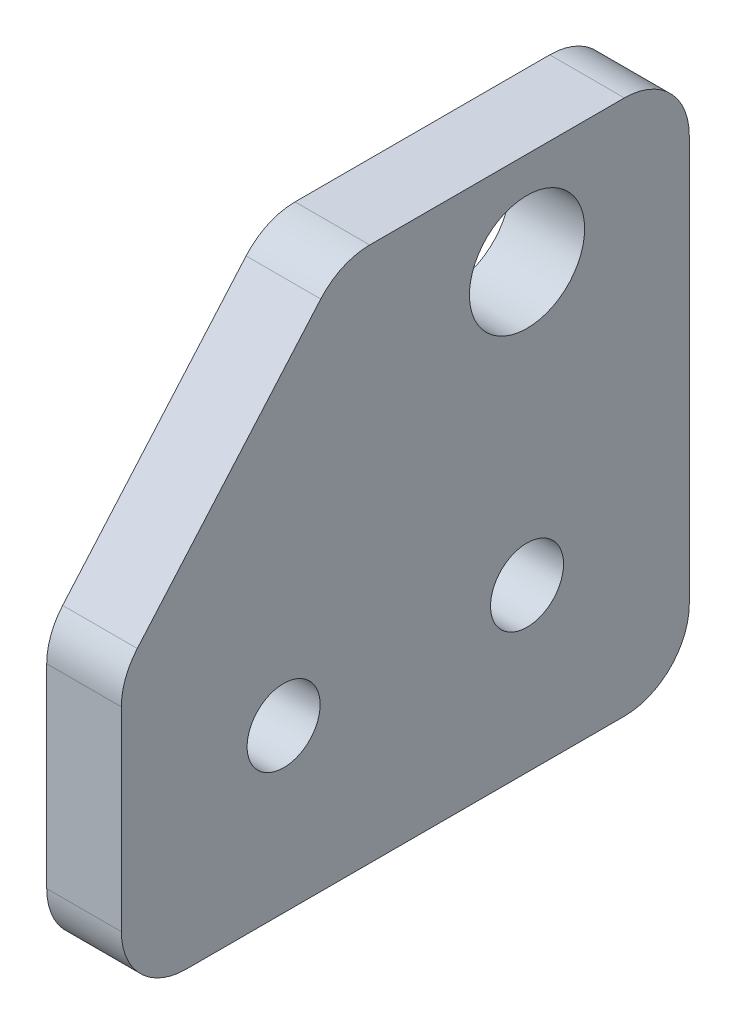
SolidWorks part; units mm, degrees
ref_plane "Front Plane" through (0, 0, 0) normal (0, 0, 1) x (1, 0, 0)
ref_plane "Top Plane" through (0, 0, 0) normal (0, 1, 0) x (1, 0, 0)
ref_plane "Right Plane" through (0, 0, 0) normal (1, 0, 0) x (0, 0, -1)
sketch "Sketch1" plane through (0, 0, 0) normal (1, 0, 0) x (0, 0, -1)
  line L0 (0, -10) -> (0, 23) construction
  line L1 (10, 0) -> (-25, 0) construction
  line L2 (-21, -10) -> (6, -10)
  line L3 (10, -6) -> (10, 19)
  line L4 (6, 23) -> (-9.6957, 23)
  line L5 (-12.7141, 21.6247) -> (-24.0184, 8.6247)
  line L6 (-25, 6) -> (-25, -6)
  line L7 (0, 17.25) -> (-15, 0) construction
  circle A0 centre (0, 0) radius 2 construction
  circle A1 centre (0, 17.25) radius 3.3 construction
  circle A2 centre (-15, 0) radius 2.25
  circle A3 centre (0, 17.25) radius 3.55
  circle A4 centre (0, 0) radius 2.25
  arc A5 (6, -10) -> (10, -6) centre (6, -6) ccw
  arc A6 (10, 19) -> (6, 23) centre (6, 19) ccw
  arc A7 (-9.6957, 23) -> (-12.7141, 21.6247) centre (-9.6957, 19) ccw
  arc A8 (-24.0184, 8.6247) -> (-25, 6) centre (-21, 6) ccw
  arc A9 (-25, -6) -> (-21, -10) centre (-21, -6) ccw
  point P30 (-25, 0)
  dimension "D2" = 6.6
  dimension "D3" = 4
  dimension "D10" = 4
  dimension "D5" = 15
  dimension "D6" = 17.25
  dimension "D7" = 10
  dimension "D8" = 10
  dimension "D9" = 5.75
  dimension "D11" = 10
  dimension "D1" = 0.25
  dimension "D4" = 0.25
extrude "Boss-Extrude1" add sketch "Sketch1" along normal blind 4.6
equation "\"Tolerance\"=0.25"
equation "\"D1@Sketch1\"=\"Tolerance\""
equation "\"D4@Sketch1\"=\"Tolerance\""
